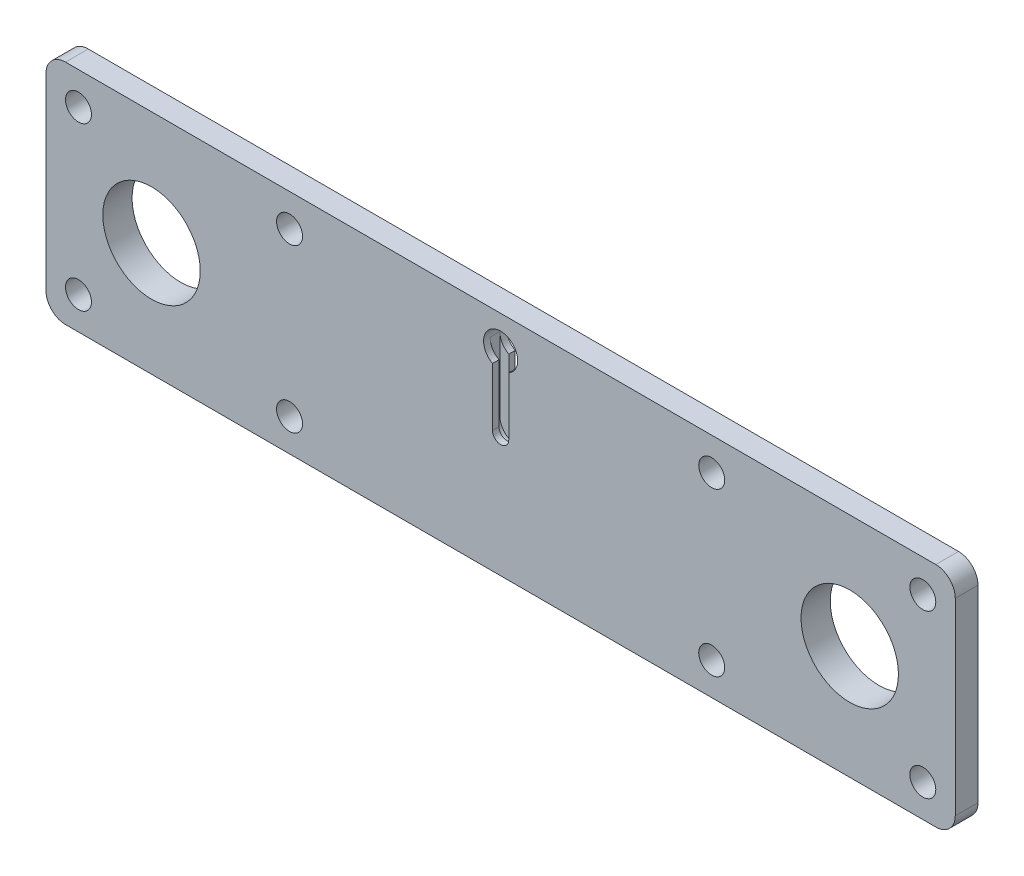
SolidWorks part; units mm, degrees
ref_plane "Ön Düzlem" through (0, 0, 0) normal (0, 0, 1) x (1, 0, 0)
ref_plane "Üst Düzlem" through (0, 0, 0) normal (0, 1, 0) x (1, 0, 0)
ref_plane "Sağ Düzlem" through (0, 0, 0) normal (1, 0, 0) x (0, 0, -1)
sketch "Sketch1" plane through (0, 0, 0) normal (0, 0, 1) x (1, 0, 0)
  line L1 (-140, 35) -> (140, 35)
  line L2 (-140, 35) -> (-140, -35)
  line L3 (-140, -35) -> (140, -35)
  line L4 (140, 35) -> (140, -35)
  line L5 (-140, 35) -> (140, -35) construction
  line L6 (-140, -35) -> (140, 35) construction
  point P0 (0, 0)
  dimension "D1" = 70
  dimension "D2" = 280
extrude "Boss-Extrude1" add sketch "Sketch1" along normal blind 7
fillet "Fillet1" radius 6 4 edges at (140, -35, 3.5) (140, 35, 3.5) (-140, -35, 3.5) (-140, 35, 3.5)
sketch "Sketch2" plane through (0, 0, 0) normal (0, 0, -1) x (-1, 0, 0)
  line L0 (-140, -29) -> (-140, 29) construction
  line L1 (140, 29) -> (140, -29) construction
  line L2 (-134, 35) -> (134, 35) construction
  line L3 (0, 2.5) -> (0, 19.75) construction
  line L4 (107.5, 0) -> (-107.5, 0) construction
  line L5 (130, 25) -> (0, 25) construction
  line L6 (130, 25) -> (130, -25) construction
  line L7 (130, -25) -> (-130, -25) construction
  line L8 (-130, 25) -> (-130, -25) construction
  line L9 (130, 25) -> (-130, -25) construction
  line L10 (130, -25) -> (-130, 25) construction
  line L11 (-2.5, 2.5) -> (-2.5, 20.3835)
  line L12 (2.5, 2.5) -> (2.5, 20.3835)
  circle A0 centre (-107.5, 0) radius 15
  circle A1 centre (107.5, 0) radius 15
  circle A2 centre (130, 25) radius 4
  circle A3 centre (65, 25) radius 4
  arc A4 (2.5, 20.3835) -> (-2.5, 20.3835) centre (0, 25) ccw
  circle A5 centre (-65, 25) radius 4
  circle A6 centre (-130, 25) radius 4
  circle A7 centre (-130, -25) radius 4
  circle A8 centre (-65, -25) radius 4
  arc A9 (-2.5, 2.5) -> (2.5, 2.5) centre (0, 2.5) ccw
  circle A10 centre (65, -25) radius 4
  circle A11 centre (130, -25) radius 4
  arc A20 (2.6458, 22) -> (-2.6458, 22) centre (0, 25) ccw [skipped]
  point P9 (140, 0)
  point P10 (0, 0)
  point P34 (0, 12.5)
  dimension "D1" = 32.5
  dimension "D2" = 30
  dimension "D3" = 32.5
  dimension "D4" = 30
  dimension "D5" = 10
  dimension "D6" = 10
  dimension "D7" = 8
  dimension "D8" = 5
  dimension "D9" = 10.5
  dimension "D10" = 5
extrude "Cut-Extrude1" cut sketch "Sketch2" against normal blind 10
sketch "Sketch3" plane through (0, 0, 0) normal (0, 0, -1) x (-1, 0, 0)
  circle A0 centre (-107.5, 0) radius 15
  circle A1 centre (-107.5, 0) radius 20
  circle A2 centre (107.5, 0) radius 15
  circle A3 centre (107.5, 0) radius 20
  dimension "D1" = 40
  dimension "D2" = 40
extrude "Boss-Extrude2" add sketch "Sketch3" along normal blind 2
ref_plane "Plane1" through (0, 0, 2) normal (0, 0, -1) x (-1, 0, 0)
sketch "Sketch4" plane through (0, 0, 2) normal (0, 0, -1) x (-1, 0, 0)
  line L3 (0, 25) -> (-5.25, 25)
  line L4 (5.25, 2.5) -> (5.25, 20.3835)
  line L5 (-5.25, 20.3835) -> (-5.25, 2.5)
  line L6 (5.25, 2.5) -> (5.25, 25)
  line L7 (-5.25, 25) -> (-5.25, 2.5)
  line L8 (0, 25) -> (5.25, 25)
  arc A2 (-5.25, 2.5) -> (5.25, 2.5) centre (0, 2.5) ccw
  arc A3 (-5.25, 2.5) -> (5.25, 2.5) centre (0, 2.5) ccw
  point P1 (-12.2974, 25)
  point P3 (-5.25, 30.5541)
  point P6 (5.25, 29.7581)
  dimension "D1" = 2.75
extrude "Cut-Extrude2" cut sketch "Sketch4" against normal blind 3
